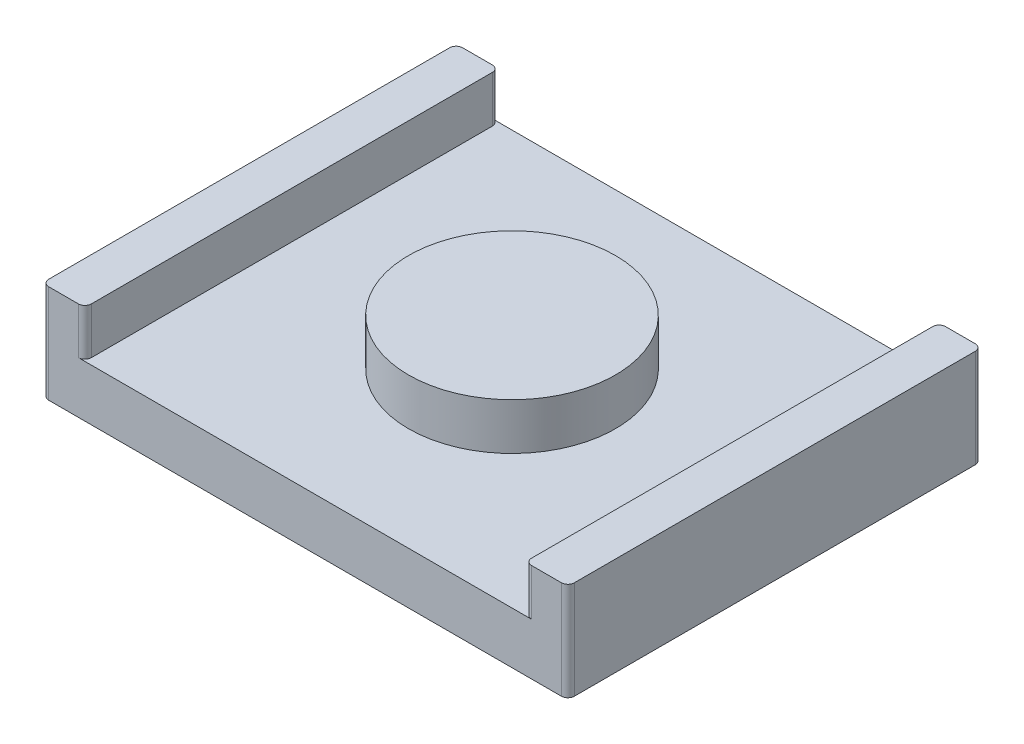
SolidWorks part; units mm, degrees
ref_plane "Front Plane" through (0, 0, 0) normal (0, 0, 1) x (1, 0, 0)
ref_plane "Top Plane" through (0, 0, 0) normal (0, 1, 0) x (1, 0, 0)
ref_plane "Right Plane" through (0, 0, 0) normal (1, 0, 0) x (0, 0, -1)
sketch "Sketch1" plane through (0, 0, 0) normal (0, 1, 0) x (1, 0, 0)
  line L1 (-20.32, -16) -> (20.32, -16)
  line L2 (-20.32, -16) -> (-20.32, 16)
  line L3 (-20.32, 16) -> (20.32, 16)
  line L4 (20.32, -16) -> (20.32, 16)
  line L5 (-20.32, -16) -> (20.32, 16) construction
  line L6 (-20.32, 16) -> (20.32, -16) construction
  point P0 (0, 0)
  dimension "D1" = 32
  dimension "D2" = 40.64
extrude "Boss-Extrude1" add sketch "Sketch1" along normal blind 4
sketch "Sketch2" plane through (0, 4, 0) normal (0, 1, 0) x (1, 0, 0)
  line L0 (-20.32, -16) -> (20.32, 16) construction
  circle A0 centre (0, 0) radius 8
  dimension "D1" = 16
extrude "Boss-Extrude2" add sketch "Sketch2" along normal blind 3.6 contours A0
sketch "Sketch3" plane through (0, 4, 0) normal (0, 1, 0) x (1, 0, 0)
  line L0 (-20.32, -16) -> (20.32, -16) construction
  line L1 (-20.32, 16) -> (-17.02, 16)
  line L2 (-20.32, 16) -> (-20.32, -16)
  line L3 (-20.32, -16) -> (-17.02, -16)
  line L4 (-17.02, 16) -> (-17.02, -16)
  dimension "D1" = 3.3
extrude "Boss-Extrude3" add sketch "Sketch3" along normal up to surface (3.6 mm away) up to face at (0, 7.6, 8)
mirror "Mirror1" about plane through (0, 0, 0) normal (1, 0, 0) of "Boss-Extrude3"
fillet "Fillet1" radius 0.5 8 edges at (17.02, 5.8, 16) (-17.02, 5.8, 16) (-17.02, 5.8, -16) (17.02, 5.8, -16) (-20.32, 3.8, -16) (20.32, 3.8, -16) (20.32, 3.8, 16) (-20.32, 3.8, 16)
